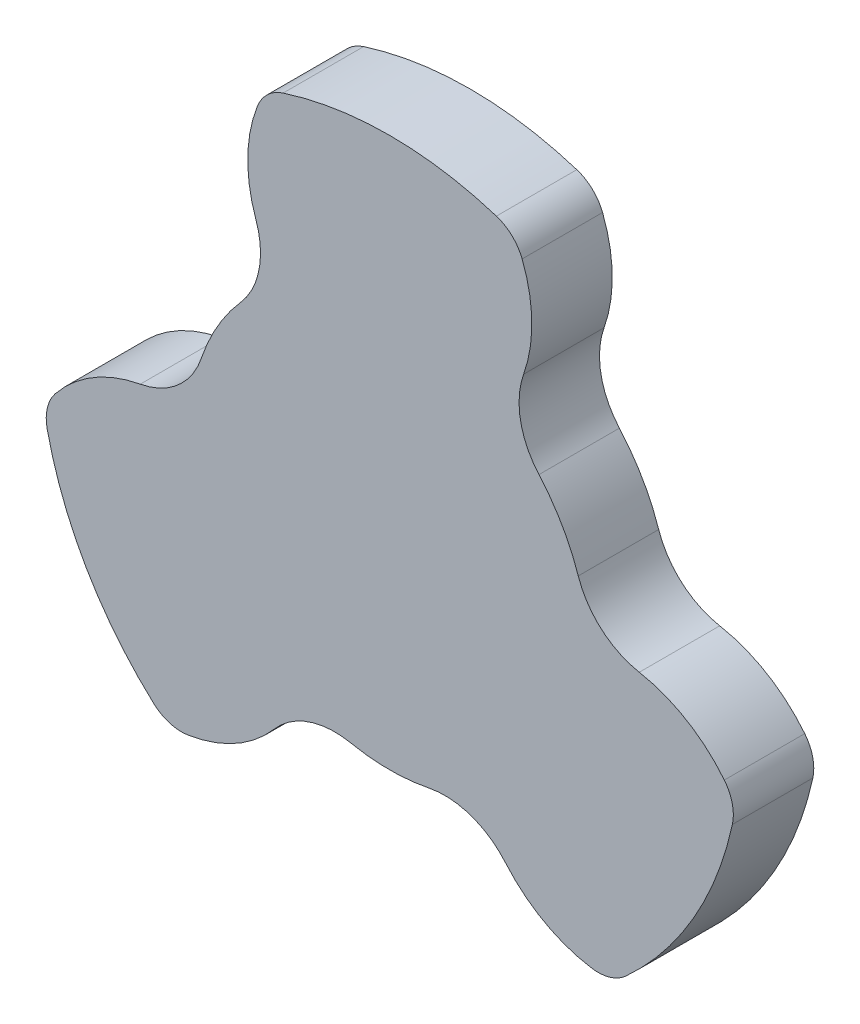
SolidWorks part; units mm, degrees
ref_plane "Front Plane" through (0, 0, 0) normal (0, 0, 1) x (1, 0, 0)
ref_plane "Top Plane" through (0, 0, 0) normal (0, 1, 0) x (1, 0, 0)
ref_plane "Right Plane" through (0, 0, 0) normal (1, 0, 0) x (0, 0, -1)
sketch "Sketch1" plane through (0, 0, 0) normal (0, 0, 1) x (1, 0, 0)
  arc A48 (19.0956, -27.2865) -> (12.381, -31.2996) centre (21.1301, -38.3145) ccw
  arc A49 (12.381, -31.2996) -> (11.7435, -34.0154) centre (14.9076, -33.3254) ccw
  arc A50 (11.7435, -34.0154) -> (20.1599, -48.5931) centre (38.7937, -28.1164) ccw
  arc A51 (20.1599, -48.5931) -> (22.8306, -49.3989) centre (22.3395, -46.1979) ccw
  arc A52 (22.8306, -49.3989) -> (29.6634, -45.5904) centre (21.1301, -38.3145) ccw
  arc A53 (35.6898, -43.5068) -> (29.6634, -45.5904) centre (34.447, -49.6693) ccw
  arc A54 (35.6898, -43.5068) -> (41.8976, -43.5068) centre (38.7937, -28.1164) ccw
  arc A55 (47.9241, -45.5904) -> (41.8976, -43.5068) centre (43.1404, -49.6693) ccw
  arc A56 (47.9241, -45.5904) -> (54.7568, -49.3989) centre (56.4574, -38.3145) ccw
  arc A57 (54.7568, -49.3989) -> (57.4276, -48.5931) centre (55.2479, -46.1979) ccw
  arc A58 (57.4276, -48.5931) -> (65.844, -34.0154) centre (38.7937, -28.1164) ccw
  arc A59 (65.844, -34.0154) -> (65.2065, -31.2996) centre (62.6798, -33.3254) ccw
  arc A60 (65.2065, -31.2996) -> (58.4919, -27.2865) centre (56.4574, -38.3145) ccw
  arc A61 (53.6742, -23.1092) -> (58.4919, -27.2865) centre (59.6324, -21.1043) ccw
  arc A62 (53.6742, -23.1092) -> (50.5703, -17.7331) centre (38.7937, -28.1164) ccw
  arc A63 (49.3615, -11.4722) -> (50.5703, -17.7331) centre (55.2857, -13.5756) ccw
  arc A64 (49.3615, -11.4722) -> (49.2434, -3.6507) centre (38.7937, -7.7202) ccw
  arc A65 (49.2434, -3.6507) -> (47.2101, -1.7407) centre (46.2256, -4.8259) ccw
  arc A66 (47.2101, -1.7407) -> (30.3773, -1.7407) centre (38.7937, -28.1164) ccw
  arc A67 (30.3773, -1.7407) -> (28.3441, -3.6507) centre (31.3618, -4.8259) ccw
  arc A68 (28.3441, -3.6507) -> (28.2259, -11.4722) centre (38.7937, -7.7202) ccw
  arc A69 (27.0172, -17.7331) -> (28.2259, -11.4722) centre (22.3018, -13.5756) ccw
  arc A70 (27.0172, -17.7331) -> (23.9133, -23.1092) centre (38.7937, -28.1164) ccw
  arc A71 (19.0956, -27.2865) -> (23.9133, -23.1092) centre (17.9551, -21.1043) ccw
extrude "Boss-Extrude1" add sketch "Sketch1" along normal blind 6.35 contours A48 A49 A50 A51 A52 A53 A54 A55 A56 A57 A58 A59 A60 A61 A62 A63 A64 A65 A66 A67 A68 A69 A70 A71
